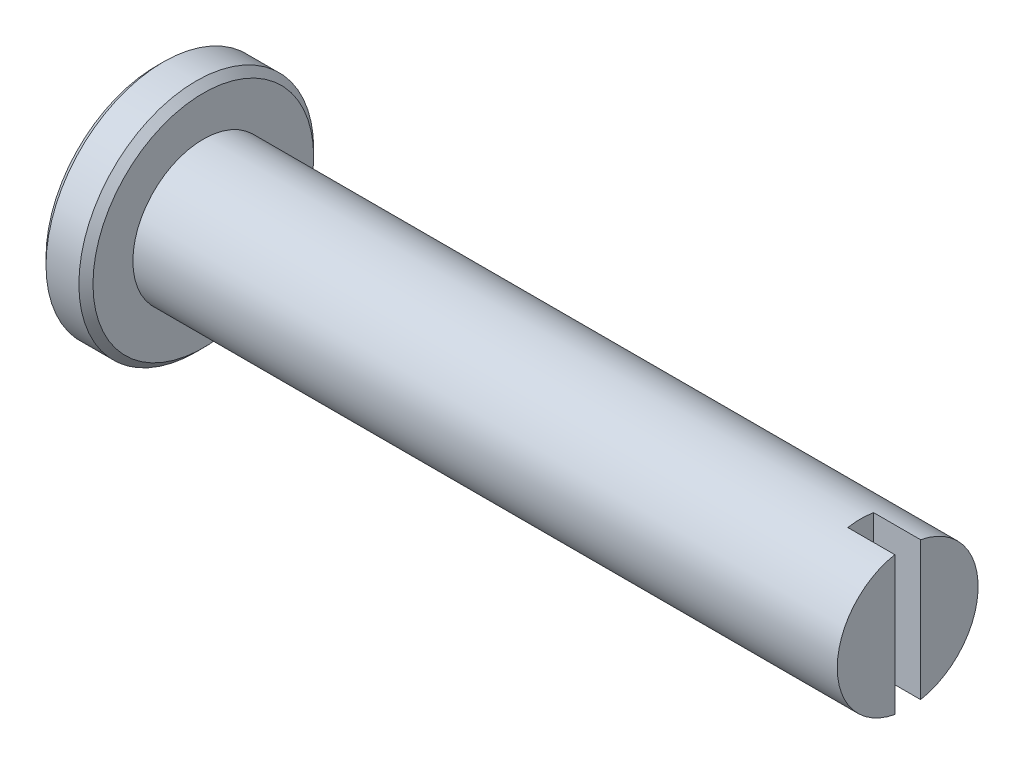
SolidWorks part; units mm, degrees
material "AISI 1020"
ref_plane "Plano superior" through (0, 0, 0) normal (0, 0, 1) x (1, 0, 0)
ref_plane "Plano frontal" through (0, 0, 0) normal (0, 1, 0) x (1, 0, 0)
ref_plane "Plano direito" through (0, 0, 0) normal (1, 0, 0) x (0, 0, -1)
sketch "Esboço1" plane through (0, 0, 0) normal (0, 1, 0) x (1, 0, 0)
  line L0 (0, 0) -> (32, 0)
  line L1 (32, 0) -> (32, 3)
  line L2 (32, 3) -> (2, 3)
  line L3 (2, 3) -> (2, 5)
  line L4 (2, 5) -> (0, 5)
  line L5 (0, 5) -> (0, 0)
  dimension "D1" = 32
  dimension "D2" = 2
  dimension "D3" = 5
  dimension "D4" = 3
revolve "Revolução1" add sketch "Esboço1" angle 360 about L0
cosmetic thread "Representação de rosca1" parameters "D2"=5.16
sketch "Esboço2" plane through (0, 0, 0) normal (0, 1, 0) x (1, 0, 0)
  line L0 (0, 0) -> (-2.5024, 0) construction
sketch "Esboço3" plane through (32, 0, 0) normal (1, 0, 0) x (0, 0, -1)
  line L0 (0, -3.3186) -> (0, 3.7792) construction
  line L1 (0.55, -3.3186) -> (0.55, 3.7792)
  line L2 (-0.55, -3.3186) -> (-0.55, 3.7792)
  line L4 (0.55, 3.7792) -> (-0.55, 3.7792)
  line L6 (0.55, -3.3186) -> (-0.55, -3.3186)
extrude "Corte-extrusão1" cut sketch "Esboço3" against normal blind 2
sketch "Esboço4" plane through (0, 0, 0) normal (-1, 0, 0) x (0, 0, 1)
  circle A0 centre (0, 0) radius 1
  dimension "D1" = 2
extrude "Ressalto-extrusão1" add sketch "Esboço4" against normal blind 2 separate body
sketch "Esboço8" plane through (0, 0, 0) normal (-1, 0, 0) x (0, 0, 1)
  circle A0 centre (0, 0) radius 1
  dimension "D1" = 2
extrude "Corte-extrusão2" cut sketch "Esboço8" against normal blind 2
chamfer "Chanfro2" distance 3.4 angle 30 1 edges at (0, 0, 1)
chamfer "Chanfro3" distance 0.3 angle 45 2 edges at (0, 0, 5) (2, 0, 5)
